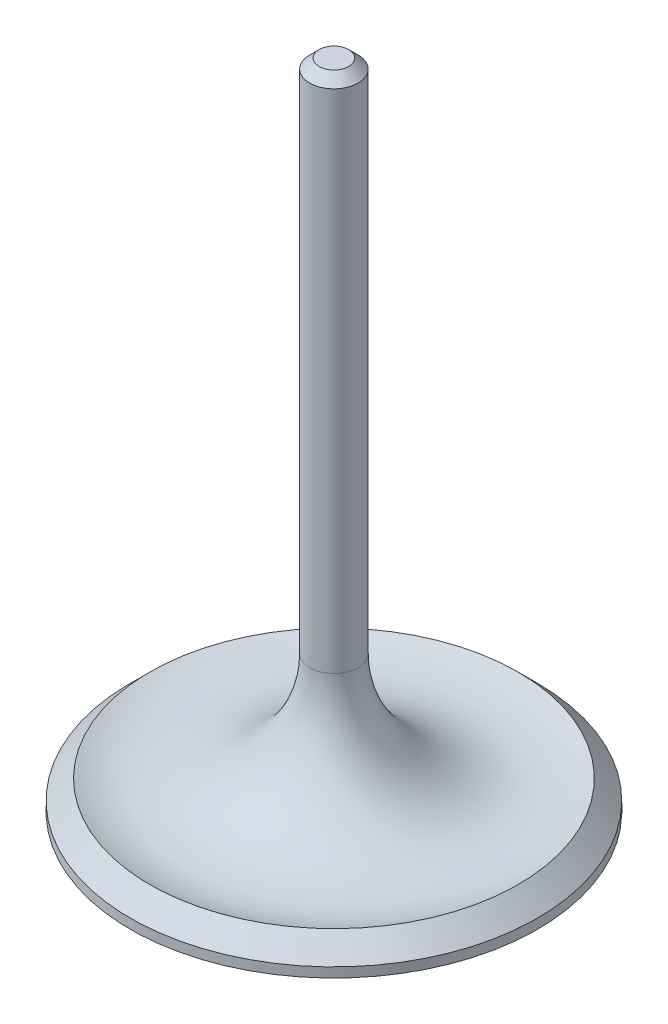
SolidWorks part; units mm, degrees
ref_plane "Front Plane" through (0, 0, 0) normal (0, 0, 1) x (1, 0, 0)
ref_plane "Top Plane" through (0, 0, 0) normal (0, 1, 0) x (1, 0, 0)
ref_plane "Right Plane" through (0, 0, 0) normal (1, 0, 0) x (0, 0, -1)
sketch "Sketch1" plane through (0, 0, 0) normal (1, 0, 0) x (0, 0, -1)
  line L0 (0, 0) -> (0, 85.55)
  line L1 (0, 85.55) -> (3.18, 85.55)
  line L2 (3.18, 85.55) -> (3.18, 17.9547)
  line L3 (26.67, 1.27) -> (26.67, 0)
  line L4 (26.67, 0) -> (0, 0)
  line L5 (24.13, 3.81) -> (26.67, 1.27)
  arc A0 (3.18, 17.9547) -> (24.13, 3.81) centre (18.43, 17.9547) ccw
  dimension "D1" = 85.55
  dimension "D4" = 3.81
  dimension "D7" = 15.25
  dimension "D2" = 26.67
  dimension "D3" = 1.27
  dimension "D5" = 45
  dimension "D6" = 3.18
revolve "Revolve1" add sketch "Sketch1" angle 360 about L0
chamfer "Chamfer1" distance 1.25 angle 45 1 edges at (0, 85.55, -3.18)
